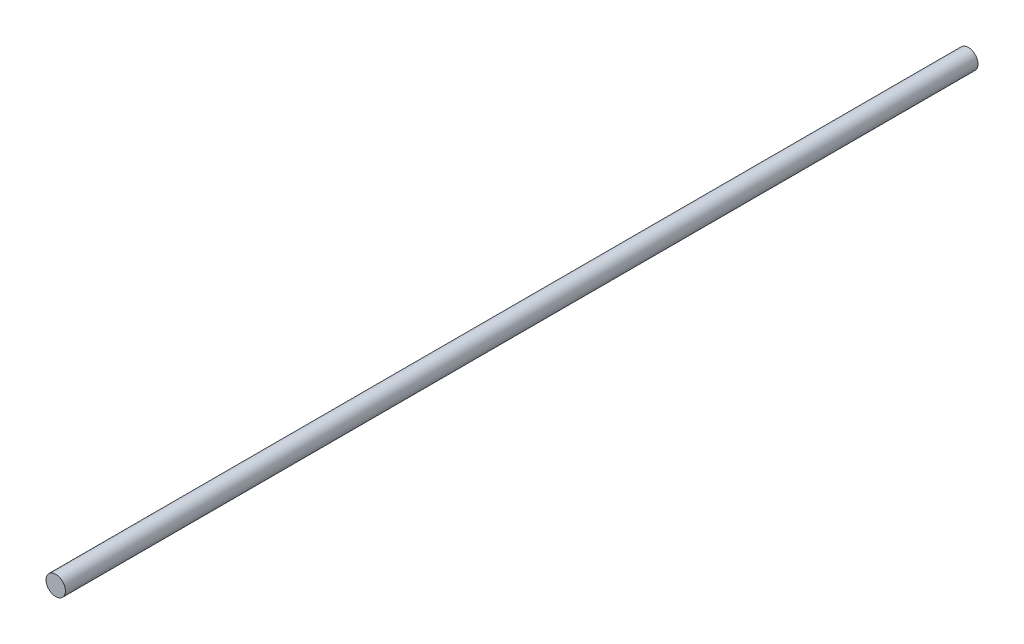
SolidWorks part; units mm, degrees
material "1023 Carbon Steel Sheet (SS)"
ref_plane "Front Plane" through (0, 0, 0) normal (0, 0, 1) x (1, 0, 0)
ref_plane "Top Plane" through (0, 0, 0) normal (0, 1, 0) x (1, 0, 0)
ref_plane "Right Plane" through (0, 0, 0) normal (1, 0, 0) x (0, 0, -1)
sketch "Sketch1" plane through (0, 0, 0) normal (0, 0, 1) x (1, 0, 0)
  circle A0 centre (0, 0) radius 6.35
  dimension "D1" = 12.7
extrude "Boss-Extrude1" add sketch "Sketch1" along normal blind 596.9
